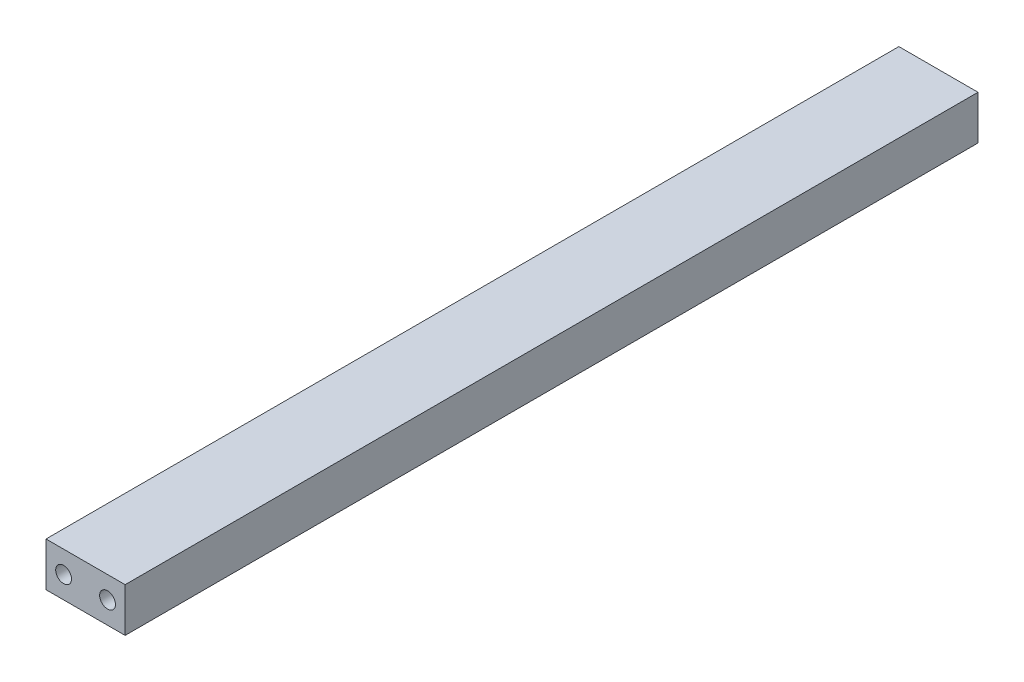
SolidWorks part; units mm, degrees
ref_plane "Front Plane" through (0, 0, 0) normal (0, 0, 1) x (1, 0, 0)
ref_plane "Top Plane" through (0, 0, 0) normal (0, 1, 0) x (1, 0, 0)
ref_plane "Right Plane" through (0, 0, 0) normal (1, 0, 0) x (0, 0, -1)
sketch "Sketch1" plane through (0, 0, 0) normal (0, 0, 1) x (1, 0, 0)
  line L5 (0, 12.7) -> (22.86, 12.7)
  line L6 (0, 12.7) -> (0, 0)
  line L7 (0, 0) -> (22.86, 0)
  line L8 (22.86, 12.7) -> (22.86, 0)
  circle A2 centre (5.08, 6.35) radius 2.286
  circle A3 centre (17.78, 6.35) radius 2.286
  dimension "D1" = 12.7
  dimension "D2" = 4.572
  dimension "D3" = 5.08
  dimension "D4" = 6.35
  dimension "D5" = 12.7
  dimension "D6" = 5.08
extrude "Boss-Extrude1" add sketch "Sketch1" against normal blind 246.38
ref_plane "Plane1" through (0, 0, -25.4) normal (0, 0, 1) x (1, 0, 0)
